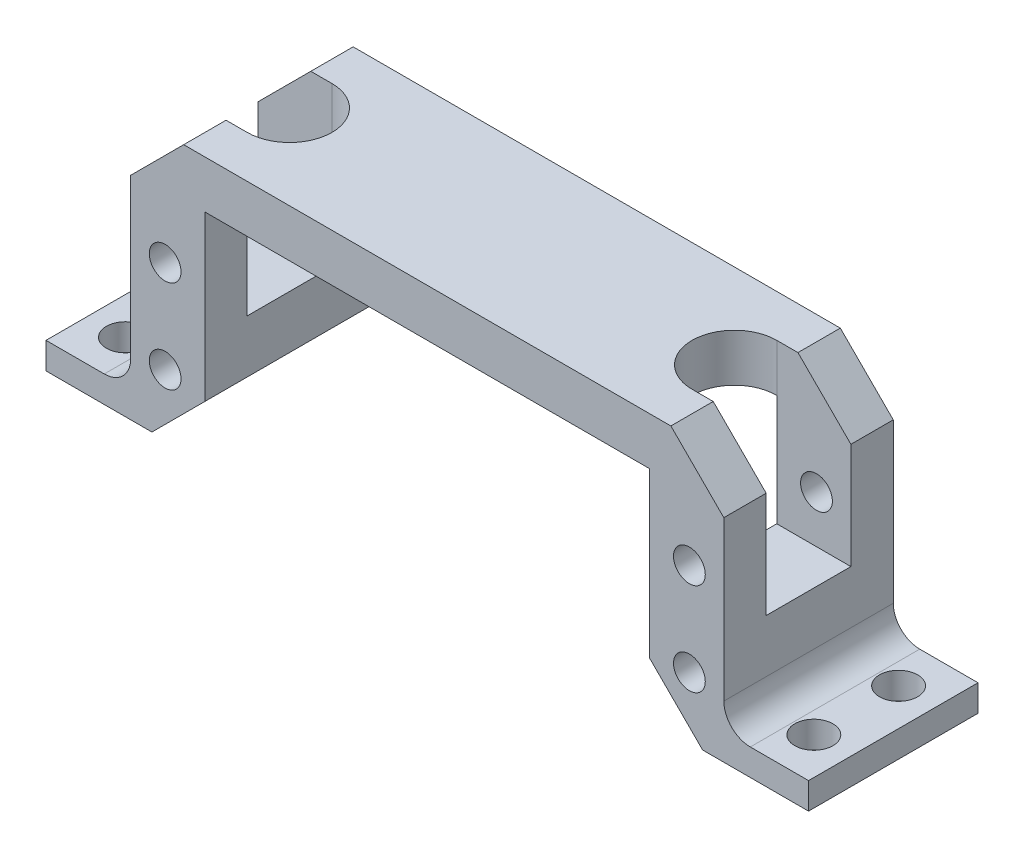
SolidWorks part; units mm, degrees
other "Markup1"
sketch "Sketch6" plane through (-36, 25, 8) normal (-0.8707, 0.2235, 0.4381) x (0.4473, -0.0107, 0.8943)
material "Nylon PA 12"
ref_plane "Front Plane" through (0, 0, 0) normal (0, 0, 1) x (1, 0, 0)
ref_plane "Top Plane" through (0, 0, 0) normal (0, 1, 0) x (1, 0, 0)
ref_plane "Right Plane" through (0, 0, 0) normal (1, 0, 0) x (0, 0, -1)
sketch "Sketch1" plane through (0, 0, 0) normal (0, 0, 1) x (1, 0, 0)
  line L0 (-36, 0) -> (-21, 0)
  line L1 (-21, 0) -> (-21, 20.5)
  line L2 (-21, 20.5) -> (21, 20.5)
  line L3 (21, 20.5) -> (21, 0)
  line L4 (21, 0) -> (36, 0)
  line L5 (-36, 0) -> (-36, 2.5)
  line L6 (-36, 2.5) -> (-28, 2.5)
  line L7 (36, 0) -> (36, 2.5)
  line L8 (36, 2.5) -> (28, 2.5)
  line L9 (-28, 2.5) -> (-28, 25)
  line L10 (-28, 25) -> (28, 25)
  line L11 (28, 25) -> (28, 2.5)
  dimension "D1" = 72
  dimension "D2" = 36
  dimension "D3" = 42
  dimension "D4" = 21
  dimension "D5" = 20.5
  dimension "D6" = 2.5
  dimension "D7" = 25
  dimension "D8" = 56
extrude "Boss-Extrude1" add sketch "Sketch1" along normal mid plane 16
chamfer "Chamfer5" distance 5 angle 45 4 edges at (-28, 25, 0) (21, 0, 0) (-21, 0, 0) (28, 25, 0)
fillet "Fillet1" radius 2.5 2 edges at (28, 2.5, 0) (-28, 2.5, 0)
sketch "Sketch2" plane through (0, 0, 8) normal (0, 0, 1) x (1, 0, 0)
  circle A0 centre (-24.75, 14.475) radius 1.5
  circle A1 centre (-24.75, 5.725) radius 1.5
  circle A2 centre (24.75, 14.475) radius 1.5
  circle A3 centre (24.75, 5.725) radius 1.5
  dimension "D1" = 3
  dimension "D5" = 14.475
  dimension "D3" = 49.5
  dimension "D4" = 24.75
  dimension "D6" = 8.75
extrude "Cut-Extrude1" cut sketch "Sketch2" against normal through all
sketch "Sketch3" plane through (0, 2.5, 0) normal (0, 1, 0) x (1, 0, 0)
  line L0 (36, -8) -> (36, 8) construction
  line L1 (30.5, 28.8859) -> (30.5, -25.0715) construction
  line L2 (-30.5, 27.8941) -> (-30.5, -24.0796) construction
  line L3 (-30.5, -8) -> (-30.5, 8) construction
  line L4 (30.5, 8) -> (30.5, -8) construction
  line L5 (56.6832, -8) -> (-41.1826, -8) construction
  line L6 (65.7079, 8) -> (-46.658, 8) construction
  line L7 (36, 8) -> (30.5, 8) construction
  line L8 (36, -8) -> (30.5, -8) construction
  line L9 (36, 29.9064) -> (36, -19.7738) construction
  circle A0 centre (32.5, 4) radius 1.8
  circle A1 centre (32.5, -4) radius 1.8
  circle A2 centre (-32.5, 4) radius 1.8
  circle A3 centre (-32.5, -4) radius 1.8
  dimension "D2" = 3.6
  dimension "D3" = 3.6
  dimension "D12" = 3.6
  dimension "D14" = 3.6
  dimension "D1" = 2
  dimension "D4" = 16
  dimension "D5" = 4
  dimension "D6" = 4
  dimension "D7" = 5.5
  dimension "D8" = 2
  dimension "D9" = 4
  dimension "D10" = 12
  dimension "D11" = 16
  dimension "D13" = 3.5
extrude "Cut-Extrude2" cut sketch "Sketch3" against normal through all
sketch "Sketch5" plane through (0, 25, 0) normal (0, 1, 0) x (1, 0, 0)
  line L0 (-28, -8) -> (-28, 8) construction
  line L6 (-32.5, 4) -> (-28, 4) construction
  line L7 (32.5, 4) -> (32.5, -4) construction
  line L8 (32.5, -4) -> (28, -4) construction
  line L9 (-32.5, -4) -> (-32.5, 4) construction
  line L13 (28, 8) -> (28, -8) construction
  line L18 (-28, -4) -> (-32.5, -4) construction
  line L21 (28, 4) -> (32.5, 4) construction
  line L32 (21, -8) -> (21, 8) construction
  line L33 (28, 4) -> (21, 4)
  line L34 (28, 4) -> (28, -4)
  line L35 (28, -4) -> (21, -4)
  line L36 (21, 4) -> (21, -4)
  line L37 (-21, -8) -> (-21, 8) construction
  line L38 (-28, 4) -> (-21, 4)
  line L39 (-28, 4) -> (-28, -4)
  line L40 (-28, -4) -> (-21, -4)
  line L41 (-21, 4) -> (-21, -4)
extrude "Cut-Extrude3" cut sketch "Sketch5" against normal blind 15
sketch "Sketch7" plane through (0, 25, 0) normal (0, 1, 0) x (1, 0, 0)
  line L0 (-23, 4) -> (-23, -4) construction
  line L1 (-21, -4) -> (-21, 4) construction
  line L2 (21, 4) -> (21, -4) construction
  line L3 (21, 4) -> (21, -4)
  line L4 (-21, 4) -> (-21, -4)
  arc A0 (-21, -4) -> (-21, 4) centre (-21, 0) ccw
  arc A1 (21, 4) -> (21, -4) centre (21, 0) ccw
extrude "Cut-Extrude5" cut sketch "Sketch7" against normal blind 15
